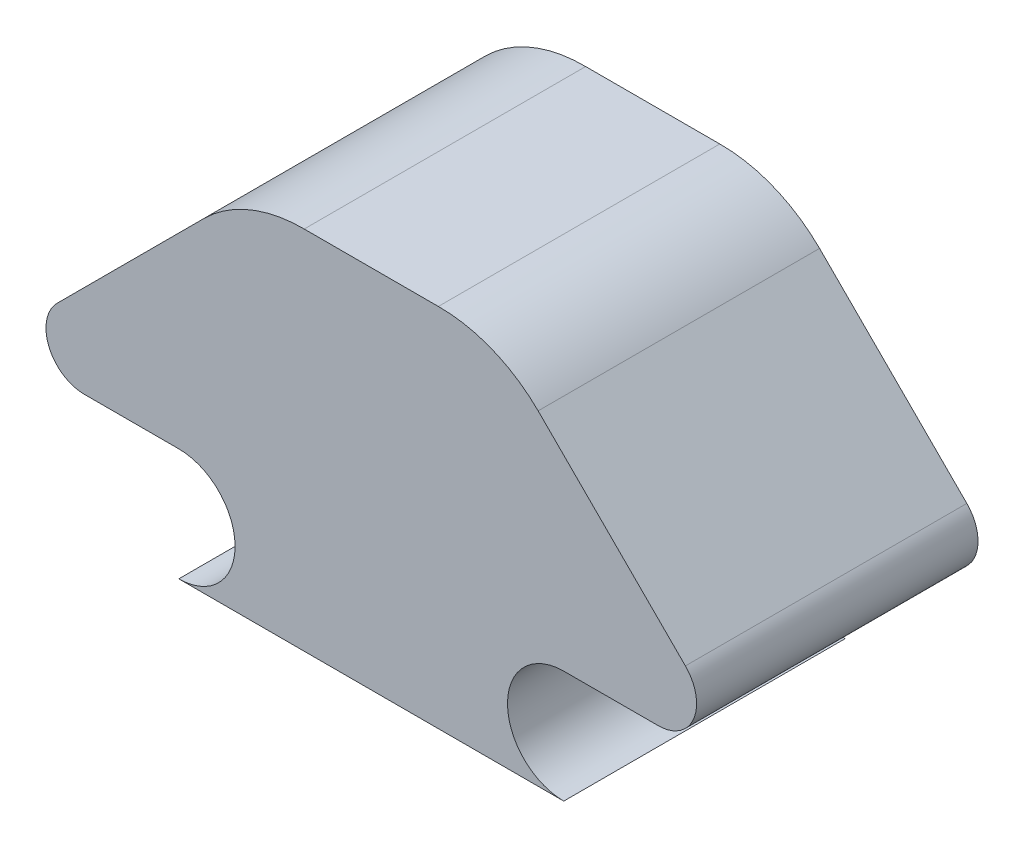
SolidWorks part; units mm, degrees
ref_plane "Front Plane" through (0, 0, 0) normal (0, 0, 1) x (1, 0, 0)
ref_plane "Top Plane" through (0, 0, 0) normal (0, 1, 0) x (1, 0, 0)
ref_plane "Right Plane" through (0, 0, 0) normal (1, 0, 0) x (0, 0, -1)
sketch "Sketch1" plane through (0, 0, 0) normal (0, 0, 1) x (1, 0, 0)
  line L0 (0, 0) -> (-4.3434, 0)
  line L1 (-4.3434, 2.54) -> (-6.477, 2.54)
  line L2 (-7.0877, 4.0143) -> (-3.765, 7.337)
  line L3 (-1.5135, 8.2512) -> (0, 8.2512)
  line L4 (0, 8.2512) -> (0, 0)
  arc A0 (-4.3434, 0) -> (-4.3434, 2.54) centre (-4.3434, 1.27) ccw
  arc A1 (-6.477, 2.54) -> (-7.0877, 4.0143) centre (-6.477, 3.4036) cw
  arc A2 (-3.765, 7.337) -> (-1.5135, 8.2512) centre (-1.5356, 5.0763) cw
extrude "Boss-Extrude1" add sketch "Sketch1" against normal blind 6.35
mirror "Mirror1" about plane through (0, 0, 0) normal (1, 0, 0) of "Boss-Extrude1"
